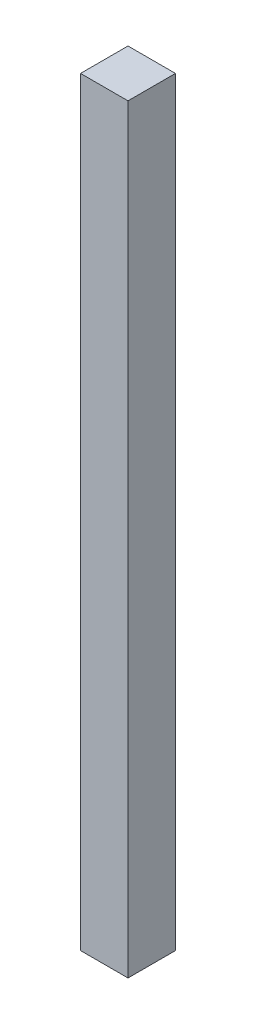
SolidWorks part; units mm, degrees
ref_plane "Front" through (0, 0, 0) normal (0, 0, 1) x (1, 0, 0)
ref_plane "Top" through (0, 0, 0) normal (0, 1, 0) x (1, 0, 0)
ref_plane "Right" through (0, 0, 0) normal (1, 0, 0) x (0, 0, -1)
sketch "Sketch1" plane through (0, 0, 0) normal (0, 1, 0) x (1, 0, 0)
  line L1 (0, 0) -> (12.7, 0)
  line L2 (0, 0) -> (0, 12.7)
  line L3 (0, 12.7) -> (12.7, 12.7)
  line L4 (12.7, 0) -> (12.7, 12.7)
  dimension "D1" = 12.7
extrude "Boss-Extrude1" add sketch "Sketch1" along normal blind 203.2
